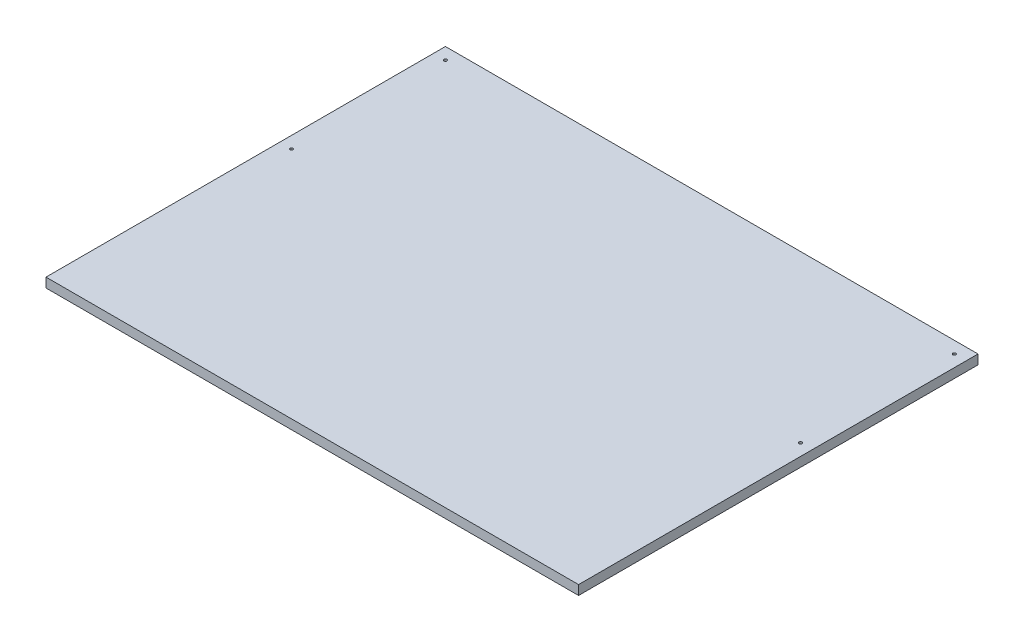
SolidWorks part; units mm, degrees
ref_plane "Спереди" through (0, 0, 0) normal (0, 0, 1) x (1, 0, 0)
ref_plane "Сверху" through (0, 0, 0) normal (0, 1, 0) x (1, 0, 0)
ref_plane "Справа" through (0, 0, 0) normal (1, 0, 0) x (0, 0, -1)
other "Configuration Table"
sketch "Эскиз1" plane through (0, 0, 0) normal (0, 1, 0) x (1, 0, 0)
  line L0 (-450, 317.5) -> (450, 317.5) construction
  line L1 (-450, -337.5) -> (450, -337.5)
  line L2 (-450, -337.5) -> (-450, 337.5)
  line L3 (-450, 337.5) -> (450, 337.5)
  line L4 (450, -337.5) -> (450, 337.5)
  line L5 (-450, -337.5) -> (450, 337.5) construction
  line L6 (-450, 337.5) -> (450, -337.5) construction
  line L7 (-430, 337.5) -> (-430, -337.5) construction
  line L8 (430, 337.5) -> (430, -337.5) construction
  line L9 (-450, 57.5) -> (450, 57.5) construction
  circle A0 centre (-430, 317.5) radius 2.5
  circle A1 centre (430, 317.5) radius 2.5
  circle A2 centre (430, 57.5) radius 2.5
  circle A3 centre (-430, 57.5) radius 2.5
  point P0 (0, 0)
  point P22 (430, 57.5)
  dimension "D7" = 5
  dimension "D1" = 900
  dimension "D2" = 20
  dimension "D3" = 20
  dimension "D4" = 20
  dimension "D5" = 675
  dimension "D6" = 280
extrude "Бобышка-Вытянуть1" add sketch "Эскиз1" along normal blind 16
